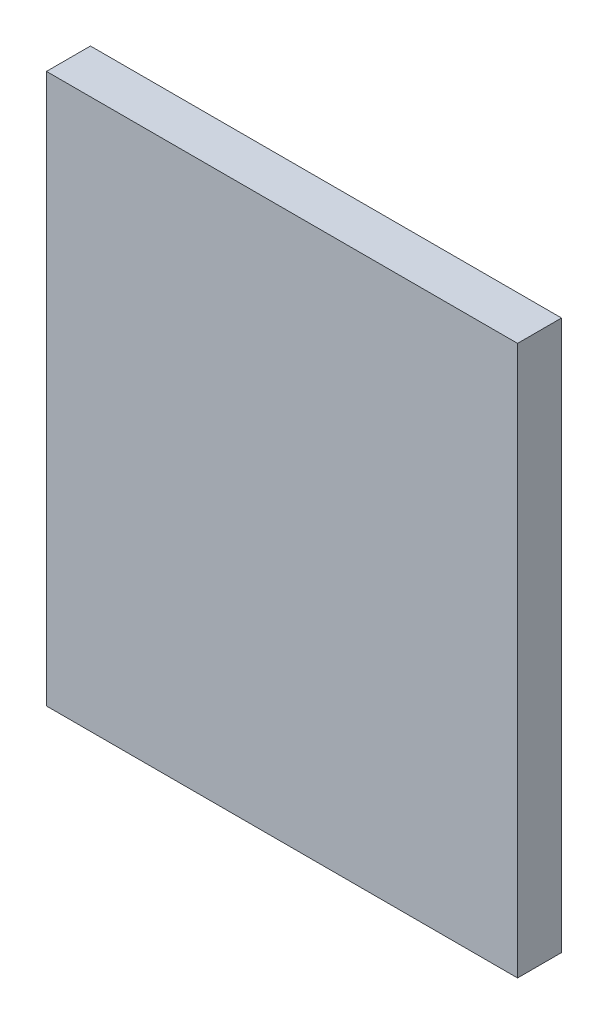
SolidWorks part; units mm, degrees
material "1060 Alloy"
ref_plane "Front Plane" through (0, 0, 0) normal (0, 0, 1) x (1, 0, 0)
ref_plane "Top Plane" through (0, 0, 0) normal (0, 1, 0) x (1, 0, 0)
ref_plane "Right Plane" through (0, 0, 0) normal (1, 0, 0) x (0, 0, -1)
sketch "Sketch1" plane through (0, 0, 0) normal (0, 0, 1) x (1, 0, 0)
  line L1 (-76.2, -88.9) -> (76.2, -88.9)
  line L2 (-76.2, -88.9) -> (-76.2, 88.9)
  line L3 (-76.2, 88.9) -> (76.2, 88.9)
  line L4 (76.2, -88.9) -> (76.2, 88.9)
  line L5 (-76.2, -88.9) -> (76.2, 88.9) construction
  line L6 (-76.2, 88.9) -> (76.2, -88.9) construction
  point P0 (0, 0)
  dimension "D1" = 152.4
  dimension "D2" = 177.8
extrude "Boss-Extrude1" add sketch "Sketch1" along normal blind 14.224
